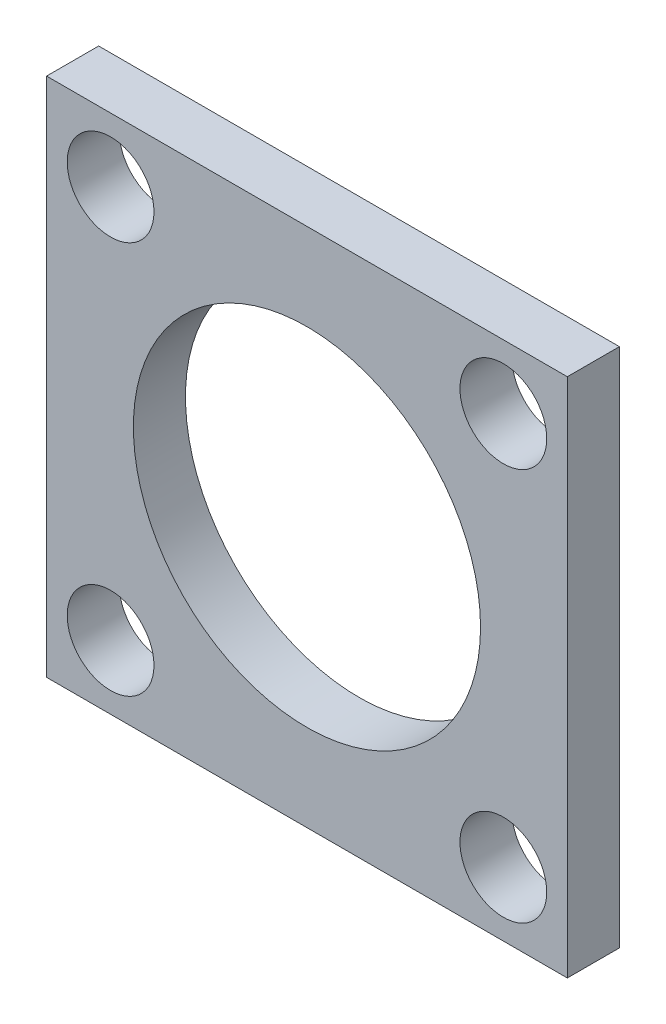
SolidWorks part; units mm, degrees
ref_plane "Front Plane" through (0, 0, 0) normal (0, 0, 1) x (1, 0, 0)
ref_plane "Top Plane" through (0, 0, 0) normal (0, 1, 0) x (1, 0, 0)
ref_plane "Right Plane" through (0, 0, 0) normal (1, 0, 0) x (0, 0, -1)
sketch "Sketch1" plane through (0, 0, 0) normal (0, 0, 1) x (1, 0, 0)
  line L1 (-15, -15) -> (15, -15)
  line L2 (-15, -15) -> (-15, 15)
  line L3 (-15, 15) -> (15, 15)
  line L4 (15, -15) -> (15, 15)
  line L5 (-15, -15) -> (15, 15) construction
  line L6 (-15, 15) -> (15, -15) construction
  point P0 (0, 0)
  dimension "D1" = 30
  dimension "D2" = 30
extrude "Boss-Extrude1" add sketch "Sketch1" along normal blind 3
sketch "Sketch2" plane through (0, 0, 3) normal (0, 0, 1) x (1, 0, 0)
  circle A0 centre (0, 0) radius 10
  dimension "D1" = 20
extrude "Cut-Extrude1" cut sketch "Sketch2" against normal blind 3
sketch "Sketch3" plane through (0, 0, 3) normal (0, 0, 1) x (1, 0, 0)
  circle A1 centre (-11.3137, 11.3137) radius 2.5
  circle A3 centre (11.3137, 11.3137) radius 2.5
  circle A4 centre (11.3137, -11.3137) radius 2.5
  circle A5 centre (-11.3137, -11.3137) radius 2.5
  point P16 (0, 0)
  dimension "D1" = 4
extrude "Cut-Extrude2" cut sketch "Sketch3" against normal blind 10
